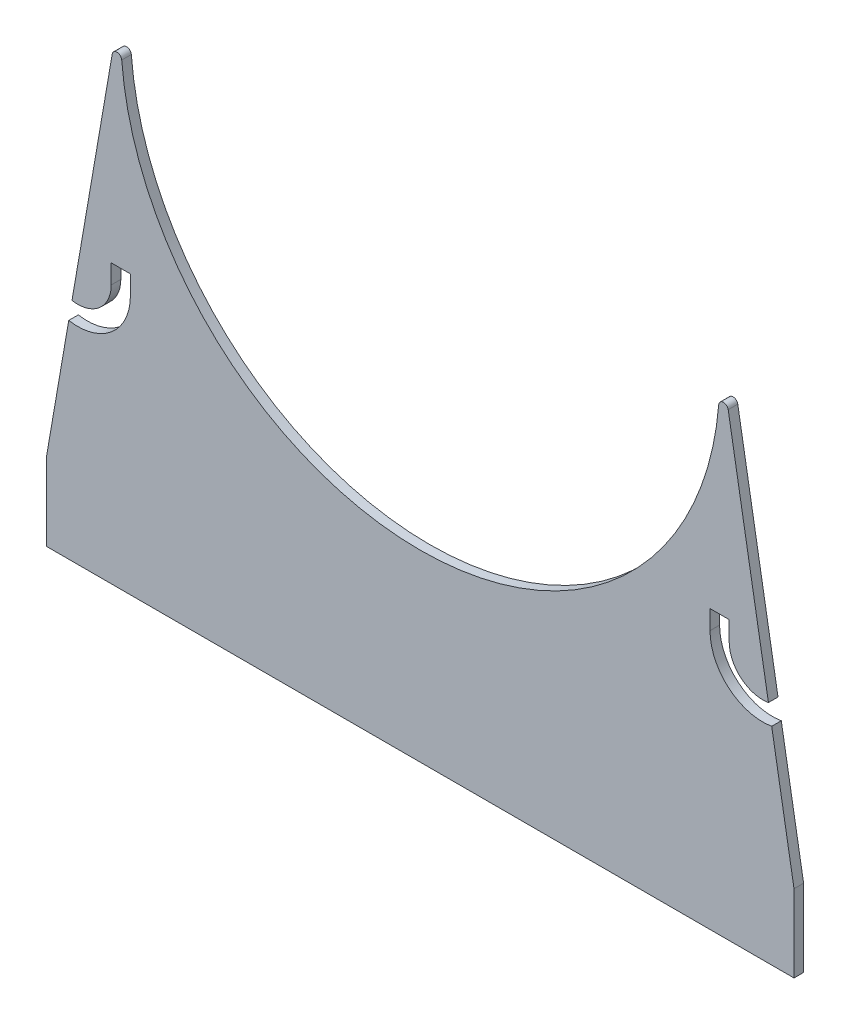
SolidWorks part; units mm, degrees
ref_plane "前视基准面" through (0, 0, 0) normal (0, 0, 1) x (1, 0, 0)
ref_plane "上视基准面" through (0, 0, 0) normal (0, 1, 0) x (1, 0, 0)
ref_plane "右视基准面" through (0, 0, 0) normal (1, 0, 0) x (0, 0, -1)
other "Configuration Table"
sketch "草图1" plane through (0, 0, 0) normal (0, 0, 1) x (1, 0, 0)
  line L0 (0, 0) -> (80, 0) construction
  line L1 (80, 0) -> (80, 9.153) construction
  line L2 (80, 9.153) -> (78.4064, 18.4) construction
  line L3 (78.4064, 18.4) -> (1.5936, 18.4) construction
  line L4 (1.5936, 18.4) -> (0, 9.153) construction
  line L5 (0, 9.153) -> (0, 0) construction
  line L6 (40, 54.4) -> (40, 18.4) construction
  line L7 (77.564, 17.4) -> (57.6635, 17.4)
  line L8 (2.436, 17.4) -> (1, 9.0674)
  line L9 (1, 9.0674) -> (1, 1)
  line L10 (1, 1) -> (79, 1)
  line L11 (79, 1) -> (79, 9.0674)
  line L12 (79, 9.0674) -> (77.564, 17.4)
  line L13 (22.3365, 17.4) -> (2.436, 17.4)
  line L14 (77.564, 17.4) -> (2.436, 17.4) construction
  circle A0 centre (40, 54.4) radius 42 construction
  arc A1 (22.3365, 17.4) -> (57.6635, 17.4) centre (40, 54.4) ccw
  circle A2 centre (40, 54.4) radius 41 construction
  dimension "D7" = 84
  dimension "D1" = 80
  dimension "D2" = 9.153
  dimension "D3" = 9.153
  dimension "D4" = 9.3834
  dimension "D5" = 9.3834
  dimension "D6" = 76.8129
  dimension "D8" = 36
  dimension "D9" = 1
extrude "凸台-拉伸1" add sketch "草图1" along normal blind 1
sketch "草图2" plane through (0, 0, 0) normal (0, 0, -1) x (-1, 0, 0)
  line L0 (-79, 9.0674) -> (-1, 9.0674) construction
  line L1 (-1, 9.0674) -> (-1, 1) construction
  text T0 "PART 4" font "Arial Narrow" height 4
extrude "凸台-拉伸2" add sketch "草图2" along normal blind 0.2
sketch "草图3" plane through (0, 0, 1) normal (0, 0, 1) x (1, 0, 0)
  line L0 (2.436, 17.4) -> (9.2097, 56.7062)
  line L1 (77.564, 17.4) -> (70.7903, 56.7062)
  line L2 (2.436, 17.4) -> (1, 9.0674) construction
  line L3 (79, 9.0674) -> (77.564, 17.4) construction
  line L4 (40, 13.4) -> (40, 51.4) construction
  line L5 (77.564, 17.4) -> (57.6635, 17.4) construction
  line L6 (22.3365, 17.4) -> (2.436, 17.4) construction
  line L7 (77.564, 17.4) -> (57.6635, 17.4)
  line L8 (22.3365, 17.4) -> (2.436, 17.4)
  arc A0 (9.2097, 56.7062) -> (70.7903, 56.7062) centre (40, 51.4) ccw
  arc A1 (22.3365, 17.4) -> (57.6635, 17.4) centre (40, 54.4) ccw construction
  arc A2 (22.3365, 17.4) -> (57.6635, 17.4) centre (40, 54.4) ccw
  point P1 (0, 0)
  dimension "D2" = 38
extrude "凸台-拉伸3" add sketch "草图3" against normal up to surface (1 mm away) up to face at (32.9802, 10.5597, 0)
sketch "草图4" plane through (0, 0, 0) normal (0, 0, -1) x (-1, 0, 0)
  line L0 (-9.2097, 56.7062) -> (-1, 9.0674) construction
  line L1 (-1, 1) -> (-79, 1) construction
  line L2 (-40, 20.1559) -> (-40, 1) construction
  line L3 (-9.3862, 30) -> (-7.7627, 30)
  line L4 (-3.6683, 24.5508) -> (-3.3286, 22.5799)
  line L5 (-9.7627, 28) -> (-9.7627, 30)
  line L6 (-7.7627, 28) -> (-7.7627, 30)
  line L7 (-9.3862, 30) -> (-9.7627, 30)
  line L8 (-70.6138, 30) -> (-70.2373, 30)
  line L9 (-72.2373, 28) -> (-72.2373, 30)
  line L10 (-70.2373, 28) -> (-70.2373, 30)
  line L11 (-76.3317, 24.5508) -> (-76.6714, 22.5799)
  line L12 (-70.6138, 30) -> (-72.2373, 30)
  arc A0 (-9.7627, 28) -> (-3.3286, 22.5799) centre (-4.2627, 28) ccw
  arc A1 (-70.7903, 56.7062) -> (-9.2097, 56.7062) centre (-40, 51.4) ccw construction
  arc A2 (-7.7627, 28) -> (-3.6683, 24.5508) centre (-4.2627, 28) ccw
  arc A3 (-72.2373, 28) -> (-76.3317, 24.5508) centre (-75.7373, 28) cw
  arc A4 (-70.2373, 28) -> (-76.6714, 22.5799) centre (-75.7373, 28) cw
  dimension "D1" = 27
  dimension "D2" = 11
  dimension "D4" = 2
  dimension "D3" = 2
extrude "切除-拉伸1" cut sketch "草图4" against normal up to next
fillet "圆角1" radius 0.5 2 edges at (9.2097, 56.7062, 0.5) (70.7903, 56.7062, 0.5)
